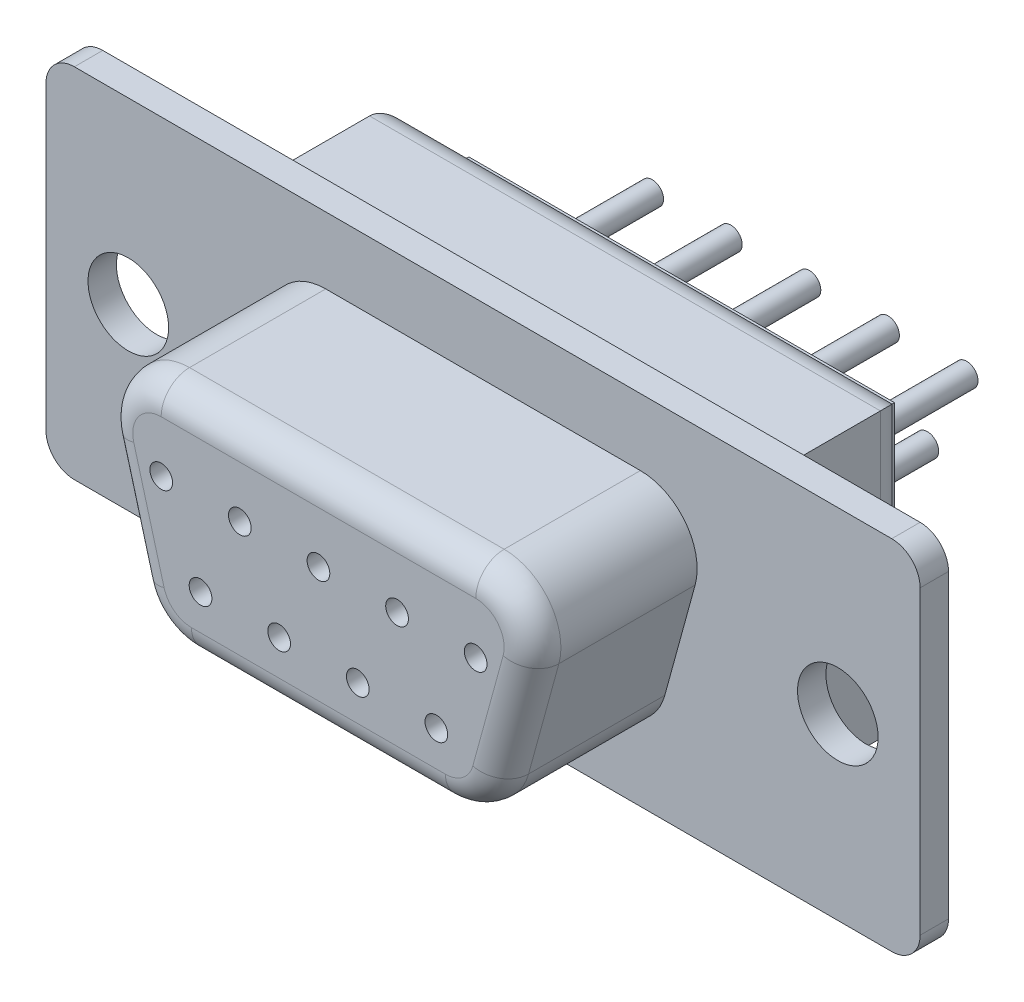
SolidWorks part; units mm, degrees
material "Нержавеющая сталь (ферритная)"
ref_plane "Front" through (0, 0, 0) normal (0, 0, 1) x (1, 0, 0)
ref_plane "Top" through (0, 0, 0) normal (0, 1, 0) x (1, 0, 0)
ref_plane "Right" through (0, 0, 0) normal (1, 0, 0) x (0, 0, -1)
sketch "Эскиз1" plane through (0, 0, 0) normal (0, 0, 1) x (1, 0, 0)
  line L1 (-15.4, 6.3) -> (15.4, 6.3)
  line L2 (-15.4, 6.3) -> (-15.4, -6.3)
  line L3 (-15.4, -6.3) -> (15.4, -6.3)
  line L4 (15.4, 6.3) -> (15.4, -6.3)
  line L5 (-15.4, 6.3) -> (15.4, -6.3) construction
  line L6 (-15.4, -6.3) -> (15.4, 6.3) construction
  point P0 (0, 0)
  dimension "D1" = 30.8
  dimension "D2" = 12.6
extrude "Бобышка-Вытянуть1" add sketch "Эскиз1" along normal blind 1
fillet "Скругление1" radius 1 4 edges at (15.4, -6.3, 0.5) (15.4, 6.3, 0.5) (-15.4, -6.3, 0.5) (-15.4, 6.3, 0.5)
sketch "Эскиз2" plane through (0, 0, 1) normal (0, 0, 1) x (1, 0, 0)
  line L0 (-8.165, 3.95) -> (8.165, 3.95)
  line L1 (8.165, 3.95) -> (6, -3.95)
  line L2 (6, -3.95) -> (-6, -3.95)
  line L3 (-6, -3.95) -> (-8.165, 3.95)
  line L4 (-15.4, 5.3) -> (-15.4, -5.3) construction
  line L5 (14.4, 6.3) -> (-14.4, 6.3) construction
  dimension "D1" = 16.33
  dimension "D2" = 7.9
  dimension "D3" = 12
  dimension "D4" = 2.165
  dimension "D5" = 7.235
  dimension "D6" = 2.35
extrude "Бобышка-Вытянуть2" add sketch "Эскиз2" along normal blind 5.8
fillet "Скругление2" radius 2 4 edges at (-6, -3.95, 3.9) (6, -3.95, 3.9) (8.165, 3.95, 3.9) (-8.165, 3.95, 3.9)
fillet "Скругление3" radius 1 8 edges at (-7.1333, 3.163, 6.8) (0, 3.95, 6.8) (7.1333, 3.163, 6.8) (6.9376, -0.5286, 6.8) (5.6874, -3.5402, 6.8) (0, -3.95, 6.8) (-5.6874, -3.5402, 6.8) (-6.9376, -0.5286, 6.8)
sketch "Эскиз3" plane through (0, 0, 1) normal (0, 0, 1) x (1, 0, 0)
  line L0 (14.4, 6.3) -> (-14.4, 6.3) construction
  line L1 (-15.4, 5.3) -> (-15.4, -5.3) construction
  circle A0 centre (-12.5, 0) radius 1.42
  circle A1 centre (12.5, 0) radius 1.42
  dimension "D1" = 25
  dimension "D2" = 6.3
  dimension "D3" = 2.9
extrude "Вырез-Вытянуть1" cut sketch "Эскиз3" against normal blind 5.8
sketch "Эскиз4" plane through (0, 0, 0) normal (0, 0, -1) x (-1, 0, 0)
  line L1 (-9, 5) -> (9, 5)
  line L2 (-9, 5) -> (-9, -5)
  line L3 (-9, -5) -> (9, -5)
  line L4 (9, 5) -> (9, -5)
  line L5 (-9, 5) -> (9, -5) construction
  line L6 (-9, -5) -> (9, 5) construction
  point P0 (0, 0)
  dimension "D1" = 18
  dimension "D2" = 10
extrude "Бобышка-Вытянуть3" add sketch "Эскиз4" along normal blind 5
fillet "Скругление4" radius 1 4 edges at (0, -5, 0) (-9, 0, 0) (0, 5, 0) (9, 0, 0)
fillet "Скругление6" radius 1 4 edges at (0, -5, -5) (9, 0, -5) (0, 5, -5) (-9, 0, -5)
sketch "Эскиз5" plane through (0, 0, -5) normal (0, 0, -1) x (-1, 0, 0)
  line L1 (-7.5, 3.5) -> (7.5, 3.5)
  line L2 (-7.5, 3.5) -> (-7.5, -3.5)
  line L3 (-7.5, -3.5) -> (7.5, -3.5)
  line L4 (7.5, 3.5) -> (7.5, -3.5)
  line L5 (-7.5, 3.5) -> (7.5, -3.5) construction
  line L6 (-7.5, -3.5) -> (7.5, 3.5) construction
  point P0 (0, 0)
  dimension "D1" = 15
  dimension "D2" = 7
extrude "Бобышка-Вытянуть4" add sketch "Эскиз5" along normal blind 1
sketch "Эскиз6" plane through (0, 0, 6.8) normal (0, 0, 1) x (1, 0, 0)
  line L0 (-15.4, 5.3) -> (-15.4, -5.3) construction
  circle A0 centre (-5.54, 1.1357) radius 0.4
  dimension "D1" = 9.86
extrude "Вырез-Вытянуть2" cut sketch "Эскиз6" against normal blind 20
pattern_linear "Линейный массив1" count 5 spacing 2.77 along (1, 0, 0) of "Вырез-Вытянуть2"
sketch "Эскиз7" plane through (0, 0, 6.8) normal (0, 0, 1) x (1, 0, 0)
  circle A0 centre (-4.155, -1.7043) radius 0.4
  circle A1 centre (-5.54, 1.1357) radius 0.4 construction
  dimension "D1" = 2.84
  dimension "D2" = 1.385
extrude "Вырез-Вытянуть3" cut sketch "Эскиз7" against normal blind 20
pattern_linear "Линейный массив2" count 4 spacing 2.77 along (1, 0, 0) of "Вырез-Вытянуть3"
sketch "Эскиз8" plane through (0, 0, -6) normal (0, 0, -1) x (-1, 0, 0)
  circle A0 centre (-5.54, 1.1357) radius 0.4
  circle A1 centre (-2.77, 1.1357) radius 0.4
  circle A2 centre (0, 1.1357) radius 0.4
  circle A3 centre (2.77, 1.1357) radius 0.4
  circle A4 centre (5.54, 1.1357) radius 0.4
  circle A5 centre (4.155, -1.7043) radius 0.4
  circle A6 centre (1.385, -1.7043) radius 0.4
  circle A7 centre (-1.385, -1.7043) radius 0.4
  circle A8 centre (-4.155, -1.7043) radius 0.4
extrude "Бобышка-Вытянуть5" add sketch "Эскиз8" along normal blind 4.5 separate body
sketch "Эскиз9" plane through (0, 0, -6) normal (0, 0, -1) x (-1, 0, 0)
  circle A0 centre (-5.54, 1.1357) radius 0.25
  circle A1 centre (-2.77, 1.1357) radius 0.25
  circle A2 centre (0, 1.1357) radius 0.25
  circle A3 centre (2.77, 1.1357) radius 0.25
  circle A4 centre (-4.155, -1.7043) radius 0.25
  circle A5 centre (-1.385, -1.7043) radius 0.25
  circle A6 centre (1.385, -1.7043) radius 0.25
  circle A7 centre (4.155, -1.7043) radius 0.25
  circle A8 centre (5.54, 1.1357) radius 0.25
extrude "Вырез-Вытянуть4" cut sketch "Эскиз9" along normal blind 4.5
